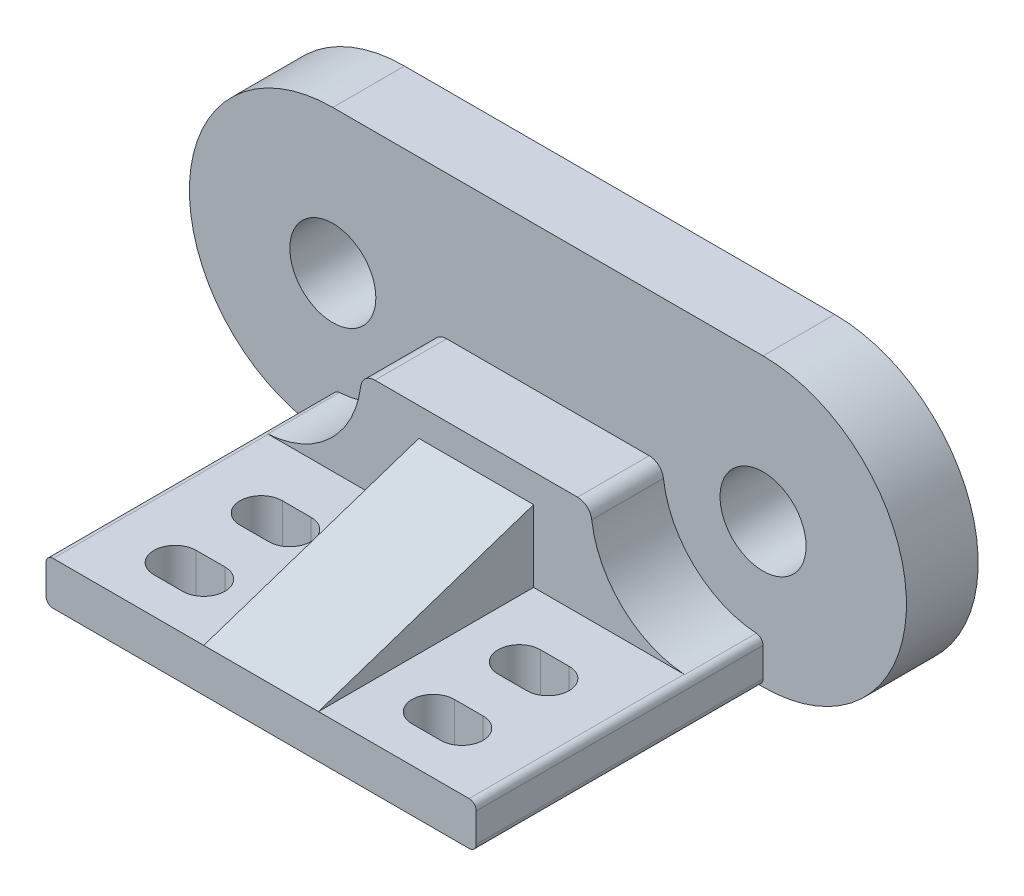
SolidWorks part; units mm, degrees
ref_plane "前视基准面" through (0, 0, 0) normal (0, 0, 1) x (1, 0, 0)
ref_plane "上视基准面" through (0, 0, 0) normal (0, 1, 0) x (1, 0, 0)
ref_plane "右视基准面" through (0, 0, 0) normal (1, 0, 0) x (0, 0, -1)
sketch "草图1" plane through (0, 0, 0) normal (0, 0, 1) x (1, 0, 0)
  line L0 (-30.44, 0) -> (32.6098, 0) construction
  line L1 (-15, 10) -> (15, 10)
  line L3 (-15, -10) -> (15, -10)
  line L5 (-15, 10) -> (15, -10) construction
  line L6 (-15, -10) -> (15, 10) construction
  arc A0 (15, 10) -> (15, -10) centre (15, 0) cw
  arc A1 (-15, 10) -> (-15, -10) centre (-15, 0) ccw
  circle A2 centre (-15, 0) radius 3
  circle A3 centre (15, 0) radius 3
  point P0 (0, 0)
  dimension "D1" = 10
  dimension "D3" = 6
  dimension "D4" = 6
  dimension "D2" = 30
extrude "凸台-拉伸1" add sketch "草图1" along normal blind 5
sketch "草图4" plane through (0, 0, 0) normal (0, 0, 1) x (1, 0, 0)
  line L0 (34.8156, 0) -> (-40.1514, 0) construction
  line L1 (0, 16.5524) -> (0, -18.2571) construction
  line L2 (7.0627, 0) -> (-7.0627, 0)
  line L3 (15, -7.4833) -> (15, -9.5)
  line L5 (-15, -7.4833) -> (-15, -9.5)
  line L6 (14.5, -10) -> (-14.5, -10)
  arc A0 (8.0549, -0.875) -> (14.5333, -6.9844) centre (15, 0) ccw
  arc A1 (-14.5333, -6.9844) -> (-8.0549, -0.875) centre (-15, 0) ccw
  arc A2 (-7.0627, 0) -> (-8.0549, -0.875) centre (-7.0627, -1) ccw
  arc A3 (-14.5333, -6.9844) -> (-15, -7.4833) centre (-14.5, -7.4833) ccw
  arc A4 (-15, -9.5) -> (-14.5, -10) centre (-14.5, -9.5) ccw
  arc A5 (15, -9.5) -> (14.5, -10) centre (14.5, -9.5) cw
  arc A6 (14.5333, -6.9844) -> (15, -7.4833) centre (14.5, -7.4833) cw
  arc A7 (7.0627, 0) -> (8.0549, -0.875) centre (7.0627, -1) cw
  dimension "D1" = 14
  dimension "D2" = 14
  dimension "D3" = 2
  dimension "D4" = 1
  dimension "D5" = 1
  dimension "D6" = 30
  dimension "D7" = 2.0167
extrude "凸台-拉伸3" add sketch "草图4" along normal blind 10
sketch "草图5" plane through (0, 0, 10) normal (0, 0, 1) x (1, 0, 0)
  line L0 (0, 14.6615) -> (0, -19.5406) construction
  line L1 (-15, -7.4833) -> (-15, -9.5)
  line L2 (15, -7.4833) -> (15, -9.5)
  line L6 (-14.5, -10) -> (14.5, -10)
  line L7 (-14.5, -6.9833) -> (14.5, -6.9833)
  line L8 (-15.6165, -9.5) -> (16.5258, -9.5) construction
  arc A0 (-14.5, -6.9833) -> (-15, -7.4833) centre (-14.5, -7.4833) ccw
  arc A1 (-15, -9.5) -> (-14.5, -10) centre (-14.5, -9.5) ccw
  arc A2 (15, -7.4833) -> (14.5, -6.9833) centre (14.5, -7.4833) ccw
  arc A4 (14.5, -10) -> (15, -9.5) centre (14.5, -9.5) ccw
extrude "凸台-拉伸4" add sketch "草图5" along normal blind 15
sketch "草图9" plane through (0, 0, 0) normal (1, 0, 0) x (0, 0, -1)
  line L0 (-25, -6.9833) -> (-10, -6.9833)
  line L1 (-10, -6.9833) -> (-10, -1.9833)
  line L2 (-10, -1.9833) -> (-25, -6.9833)
  line L3 (-10, -0.875) -> (-10, -6.9844) construction
  line L4 (-25, -6.9833) -> (-10, -6.9833) construction
  dimension "D1" = 5
  dimension "D2" = 15
extrude "凸台-拉伸5" add sketch "草图9" along normal mid plane 8
sketch "草图10" plane through (0, -6.9833, 0) normal (0, 1, 0) x (1, 0, 0)
  line L0 (0, -28.1508) -> (0, 3.4123) construction
  line L1 (15, 0) -> (-15, 0) construction
  line L2 (35.8811, -18) -> (-23.6932, -18) construction
  line L3 (35.8811, -15) -> (-21.9847, -15) construction
  line L5 (10, -13.525) -> (8, -13.525)
  line L6 (8, -16.475) -> (10, -16.475)
  line L7 (8, -19.525) -> (10, -19.525)
  line L8 (10, -22.475) -> (8, -22.475)
  line L9 (-10, -13.525) -> (-8, -13.525)
  line L10 (-8, -16.475) -> (-10, -16.475)
  line L11 (-8, -19.525) -> (-10, -19.525)
  line L12 (-10, -22.475) -> (-8, -22.475)
  arc A0 (10, -16.475) -> (10, -13.525) centre (10, -15) ccw
  arc A1 (8, -13.525) -> (8, -16.475) centre (8, -15) ccw
  arc A2 (8, -22.475) -> (8, -19.525) centre (8, -21) cw
  arc A3 (10, -19.525) -> (10, -22.475) centre (10, -21) cw
  arc A4 (-10, -16.475) -> (-10, -13.525) centre (-10, -15) cw
  arc A5 (-8, -13.525) -> (-8, -16.475) centre (-8, -15) cw
  arc A6 (-8, -22.475) -> (-8, -19.525) centre (-8, -21) ccw
  arc A7 (-10, -19.525) -> (-10, -22.475) centre (-10, -21) ccw
  point P2 (9, -16.475)
  point P19 (9, -19.525)
  dimension "D3" = 2.95
  dimension "D5" = 2
  dimension "D2" = 3
  dimension "D1" = 15
  dimension "D6" = 8
extrude "切除-拉伸1" cut sketch "草图10" against normal blind 3.5
